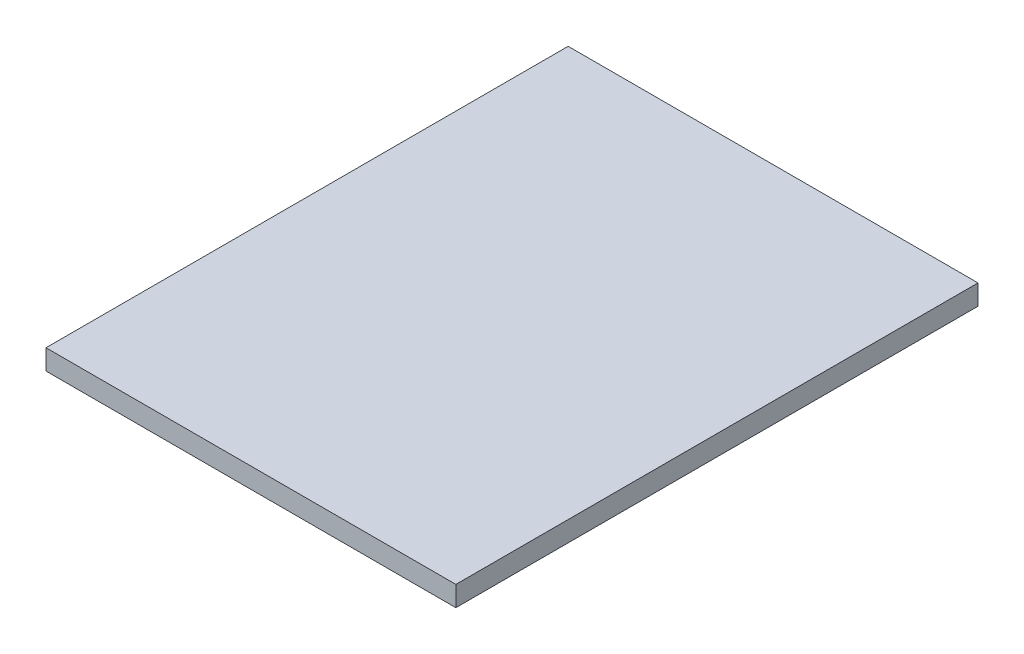
SolidWorks part; units mm, degrees
ref_plane "Спереди" through (0, 0, 0) normal (0, 0, 1) x (1, 0, 0)
ref_plane "Сверху" through (0, 0, 0) normal (0, 1, 0) x (1, 0, 0)
ref_plane "Справа" through (0, 0, 0) normal (1, 0, 0) x (0, 0, -1)
sketch "Эскиз1" plane through (0, 0, 0) normal (0, 1, 0) x (1, 0, 0)
  line L1 (-151.4284, 70.2336) -> (213.5716, 70.2336)
  line L2 (-151.4284, 70.2336) -> (-151.4284, -394.7664)
  line L3 (-151.4284, -394.7664) -> (213.5716, -394.7664)
  line L4 (213.5716, 70.2336) -> (213.5716, -394.7664)
  line L5 (-151.4284, 70.2336) -> (213.5716, -394.7664) construction
  line L6 (-151.4284, -394.7664) -> (213.5716, 70.2336) construction
  point P0 (31.0716, -162.2664)
  dimension "D1" = 365
  dimension "D2" = 465
extrude "Бобышка-Вытянуть1" add sketch "Эскиз1" along normal blind 18
